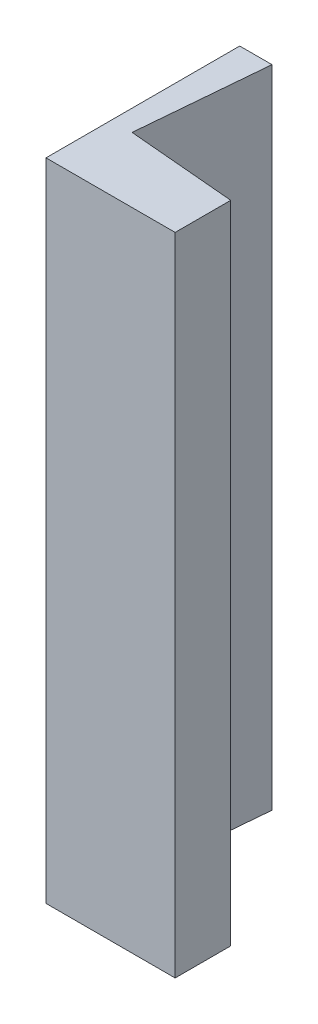
SolidWorks part; units mm, degrees
ref_plane "Front Plane" through (0, 0, 0) normal (0, 0, 1) x (1, 0, 0)
ref_plane "Top Plane" through (0, 0, 0) normal (0, 1, 0) x (1, 0, 0)
ref_plane "Right Plane" through (0, 0, 0) normal (1, 0, 0) x (0, 0, -1)
sketch "Sketch2" plane through (0, 0, 0) normal (0, 1, 0) x (1, 0, 0)
  line L0 (-6.35, 19.05) -> (-8.5638, -6.2533)
  line L1 (-12.7, -19.05) -> (12.7, -19.05)
  line L2 (-12.7, -19.05) -> (-12.7, 19.05)
  line L3 (-12.7, 19.05) -> (-6.35, 19.05)
  line L4 (12.7, -19.05) -> (12.7, -8.1137)
  line L5 (-12.7, -19.05) -> (12.7, 19.05) construction
  line L6 (-12.7, 19.05) -> (12.7, -19.05) construction
  line L7 (-8.5638, -6.2533) -> (12.7, -8.1137)
  point P1 (0, 0)
  dimension "D1" = 85
  dimension "D2" = 6.35
  dimension "D3" = 90
extrude "Boss-Extrude1" add sketch "Sketch2" along normal blind 127
